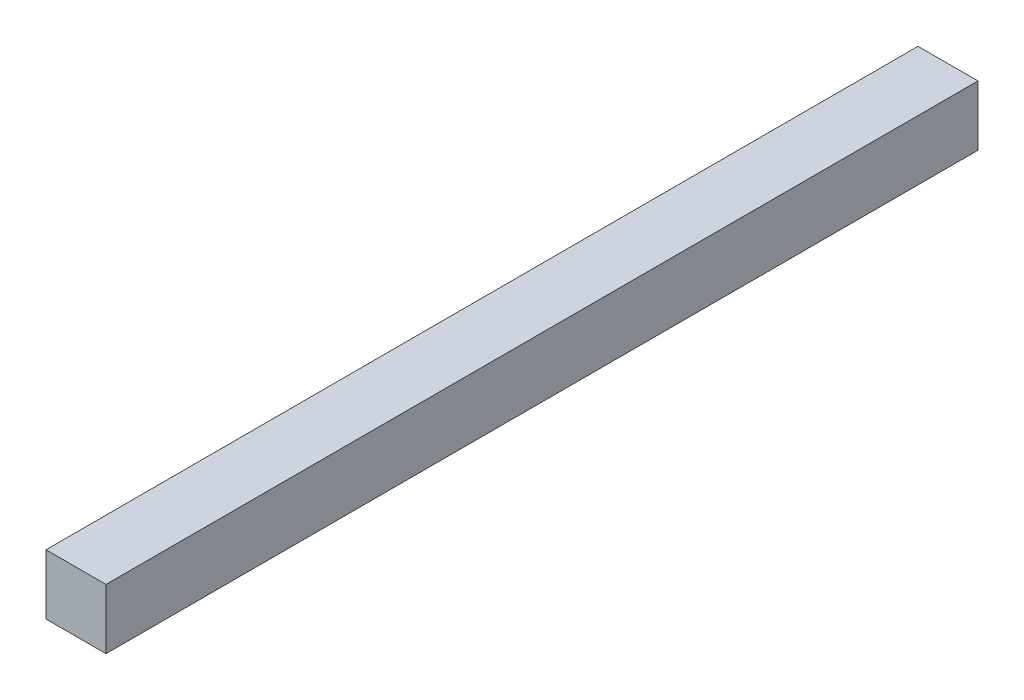
SolidWorks part; units mm, degrees
ref_plane "Front Plane" through (0, 0, 0) normal (0, 0, 1) x (1, 0, 0)
ref_plane "Top Plane" through (0, 0, 0) normal (0, 1, 0) x (1, 0, 0)
ref_plane "Right Plane" through (0, 0, 0) normal (1, 0, 0) x (0, 0, -1)
sketch "Sketch1" plane through (0, 0, 0) normal (0, 0, 1) x (1, 0, 0)
  line L1 (-19.5762, 22.7172) -> (10.4238, 22.7172)
  line L2 (-19.5762, 22.7172) -> (-19.5762, -7.2828)
  line L3 (-19.5762, -7.2828) -> (10.4238, -7.2828)
  line L4 (10.4238, 22.7172) -> (10.4238, -7.2828)
  dimension "D1" = 30
  dimension "D2" = 30
extrude "Boss-Extrude1" add sketch "Sketch1" along normal blind 436
